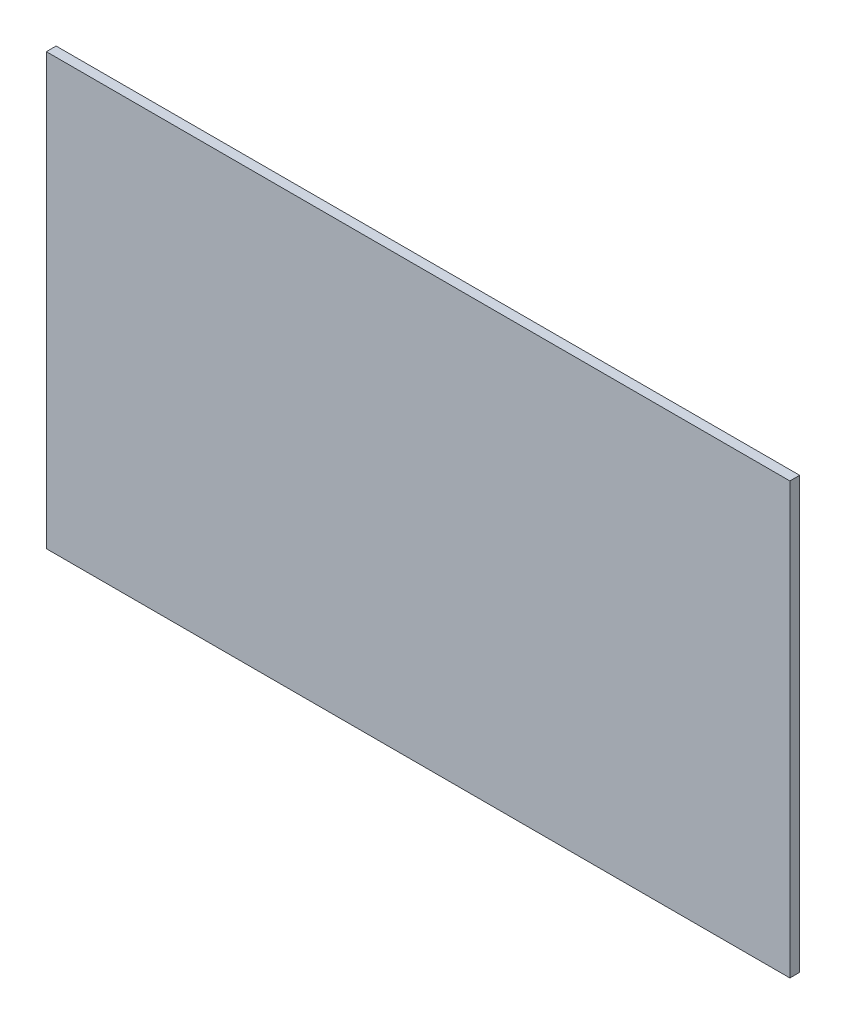
SolidWorks part; units mm, degrees
ref_plane "Plan de face" through (0, 0, 0) normal (0, 0, 1) x (1, 0, 0)
ref_plane "Plan de dessus" through (0, 0, 0) normal (0, 1, 0) x (1, 0, 0)
ref_plane "Plan de droite" through (0, 0, 0) normal (1, 0, 0) x (0, 0, -1)
sketch "Esquisse1" plane through (0, 0, 0) normal (0, 0, 1) x (1, 0, 0)
  line L1 (-189.6573, 78.6929) -> (190.3427, 78.6929)
  line L2 (-189.6573, 78.6929) -> (-189.6573, -141.3071)
  line L3 (-189.6573, -141.3071) -> (190.3427, -141.3071)
  line L4 (190.3427, 78.6929) -> (190.3427, -141.3071)
  dimension "D1" = 380
  dimension "D2" = 220
extrude "Boss.-Extru.1" add sketch "Esquisse1" along normal blind 5
